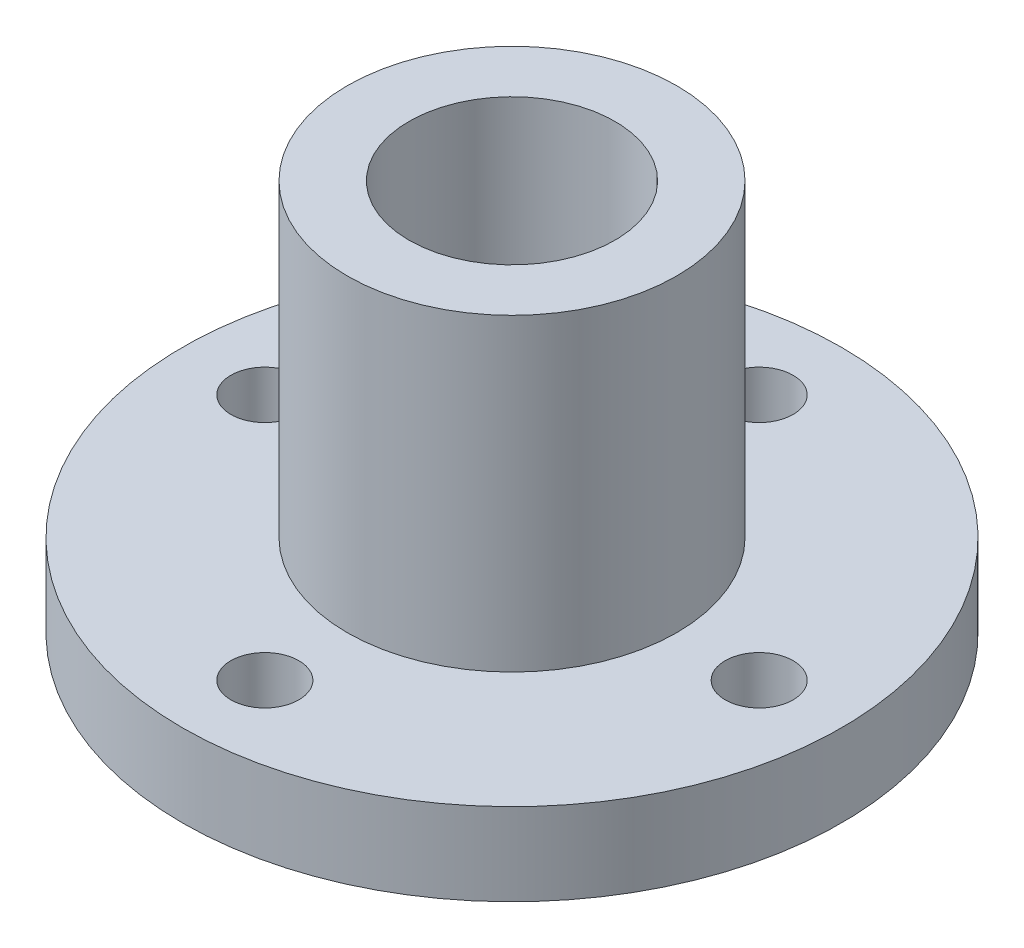
SolidWorks part; units mm, degrees
ref_plane "前视基准面" through (0, 0, 0) normal (0, 0, 1) x (1, 0, 0)
ref_plane "上视基准面" through (0, 0, 0) normal (0, 1, 0) x (1, 0, 0)
ref_plane "右视基准面" through (0, 0, 0) normal (1, 0, 0) x (0, 0, -1)
sketch "草图1" plane through (0, 0, 0) normal (0, 1, 0) x (1, 0, 0)
  circle A0 centre (0, 0) radius 8
  circle A1 centre (0, 0) radius 5
extrude "凸台-拉伸3" add sketch "草图1" along normal blind 19
sketch "草图6" plane through (0, 0, 0) normal (0, -1, 0) x (1, 0, 0)
  circle A0 centre (0, 0) radius 16
  circle A1 centre (-12, 0) radius 1.65
  circle A2 centre (0, 12) radius 1.65
  circle A3 centre (12, 0) radius 1.65
  circle A4 centre (0, -12) radius 1.65
extrude "凸台-拉伸4" add sketch "草图6" against normal blind 4
sketch "草图7" plane through (0, 4, 0) normal (0, 1, 0) x (1, 0, 0)
  circle A0 centre (0, 0) radius 5
extrude "切除-拉伸3" cut sketch "草图7" against normal blind 4
